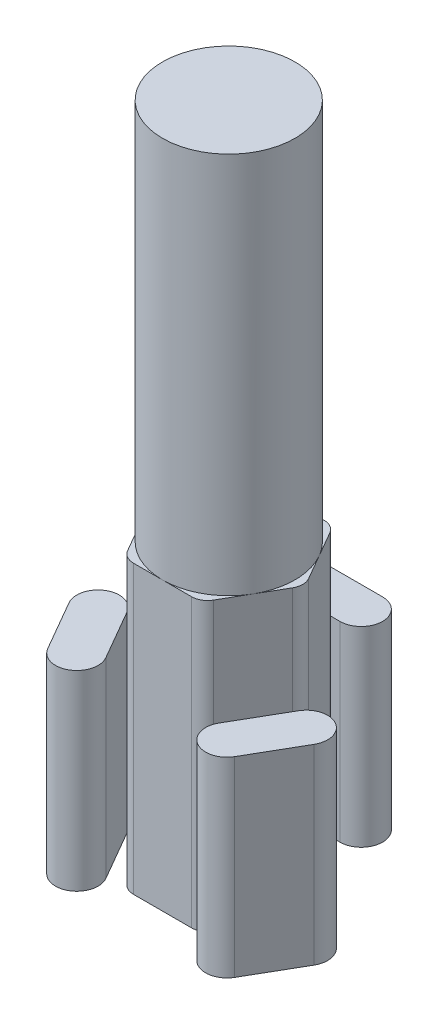
SolidWorks part; units mm, degrees
ref_plane "Front Plane" through (0, 0, 0) normal (0, 0, 1) x (1, 0, 0)
ref_plane "Top Plane" through (0, 0, 0) normal (0, 1, 0) x (1, 0, 0)
ref_plane "Right Plane" through (0, 0, 0) normal (1, 0, 0) x (0, 0, -1)
sketch "Sketch1" plane through (0, 0, 0) normal (0, 1, 0) x (1, 0, 0)
  line L0 (-0.0911, 0.2578) -> (0.0911, 0.2578)
  line L1 (-0.1344, 0.1828) -> (-0.2256, 0.025)
  line L2 (-0.2256, -0.025) -> (-0.1344, -0.1828)
  line L3 (-0.0911, -0.2078) -> (0.0911, -0.2078)
  line L4 (0.1344, -0.1828) -> (0.2256, -0.025)
  line L5 (0.2256, 0.025) -> (0.1344, 0.1828)
  line L6 (0.0911, 0.2078) -> (-0.0911, 0.2078)
  line L7 (-0.0911, 0.3914) -> (0.0911, 0.3914)
  line L8 (0, 0) -> (0.4855, 0.2803) construction
  line L9 (0.2934, -0.2746) -> (0.3846, -0.1168)
  line L10 (0.1777, -0.2078) -> (0.2689, -0.05)
  line L11 (0, 0) -> (-0.3106, 0.1793) construction
  line L12 (-0.3846, -0.1168) -> (-0.2934, -0.2746)
  line L13 (-0.2689, -0.05) -> (-0.1777, -0.2078)
  circle A0 centre (0, 0) radius 0.24 construction
  circle A1 centre (0, 0) radius 0.24 construction
  arc A2 (-0.1344, 0.1828) -> (-0.0911, 0.2078) centre (-0.0911, 0.1578) cw
  arc A3 (0.1344, 0.1828) -> (0.0911, 0.2078) centre (0.0911, 0.1578) ccw
  arc A4 (-0.2256, -0.025) -> (-0.2256, 0.025) centre (-0.1823, 0) cw
  arc A5 (-0.1344, -0.1828) -> (-0.0911, -0.2078) centre (-0.0911, -0.1578) ccw
  arc A6 (0.0911, -0.2078) -> (0.1344, -0.1828) centre (0.0911, -0.1578) ccw
  arc A7 (0.2256, -0.025) -> (0.2256, 0.025) centre (0.1823, 0) ccw
  arc A8 (-0.0911, 0.2578) -> (-0.0911, 0.3914) centre (-0.0911, 0.3246) cw
  arc A9 (0.0911, 0.2578) -> (0.0911, 0.3914) centre (0.0911, 0.3246) ccw
  arc A10 (0.2689, -0.05) -> (0.3846, -0.1168) centre (0.3267, -0.0834) cw
  arc A11 (0.1777, -0.2078) -> (0.2934, -0.2746) centre (0.2356, -0.2412) ccw
  arc A12 (-0.1777, -0.2078) -> (-0.2934, -0.2746) centre (-0.2356, -0.2412) cw
  arc A13 (-0.2689, -0.05) -> (-0.3846, -0.1168) centre (-0.3267, -0.0834) ccw
  point P12 (-0.12, 0.2078)
  dimension "D2" = 0.05
  dimension "D3" = 0.05
  dimension "D4" = 0.05
  dimension "D5" = 0.05
  dimension "D6" = 0.05
  dimension "D7" = 0.05
  dimension "D8" = 0.05
extrude "Boss-Extrude5" add sketch "Sketch1" along normal blind 0.9
sketch "Sketch4" plane through (0, 0.9, 0) normal (0, 1, 0) x (1, 0, 0)
  line L0 (-0.0911, 0.3914) -> (0.0911, 0.3914)
  line L1 (0.0911, 0.2578) -> (-0.0911, 0.2578)
  line L2 (0.2689, -0.05) -> (0.1777, -0.2078)
  line L3 (0.3846, -0.1168) -> (0.2934, -0.2746)
  line L4 (-0.1777, -0.2078) -> (-0.2689, -0.05)
  line L5 (-0.2934, -0.2746) -> (-0.3846, -0.1168)
  arc A0 (-0.0911, 0.3914) -> (-0.0911, 0.2578) centre (-0.0911, 0.3246) ccw construction
  arc A1 (-0.3846, -0.1168) -> (-0.2689, -0.05) centre (-0.3267, -0.0834) cw
  arc A2 (-0.1777, -0.2078) -> (-0.2934, -0.2746) centre (-0.2356, -0.2412) cw
  arc A3 (0.2689, -0.05) -> (0.3846, -0.1168) centre (0.3267, -0.0834) cw
  arc A4 (0.2934, -0.2746) -> (0.1777, -0.2078) centre (0.2356, -0.2412) cw
  arc A5 (0.0911, 0.2578) -> (0.0911, 0.3914) centre (0.0911, 0.3246) ccw
  arc A6 (-0.0911, 0.3914) -> (-0.0911, 0.2578) centre (-0.0911, 0.3246) ccw
extrude "Cut-Extrude2" cut sketch "Sketch4" against normal blind 0.3
sketch "Sketch5" plane through (0, 0.9, 0) normal (0, 1, 0) x (1, 0, 0)
  line L0 (-0.1344, -0.1828) -> (-0.2256, -0.025) construction
  circle A0 centre (0, 0) radius 0.2078
extrude "Boss-Extrude6" add sketch "Sketch5" along normal blind 1.2
